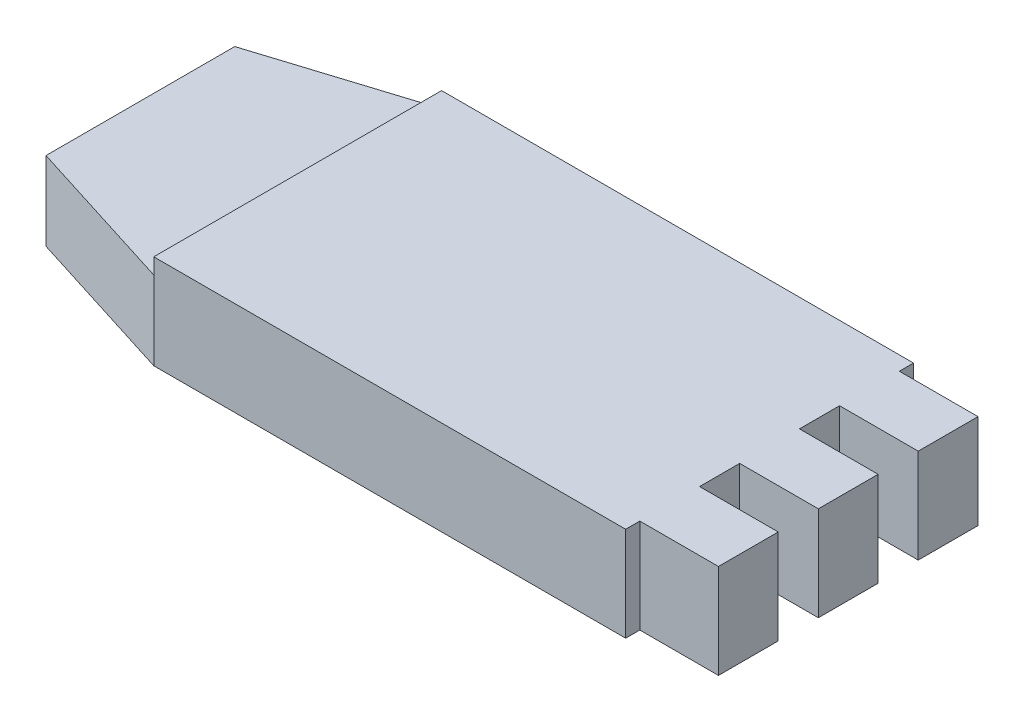
SolidWorks part; units mm, degrees
ref_plane "Front Plane" through (0, 0, 0) normal (0, 0, 1) x (1, 0, 0)
ref_plane "Top Plane" through (0, 0, 0) normal (0, 1, 0) x (1, 0, 0)
ref_plane "Right Plane" through (0, 0, 0) normal (1, 0, 0) x (0, 0, -1)
sketch "Sketch1" plane through (0, 0, 0) normal (0, 1, 0) x (1, 0, 0)
  line L0 (12.5, 9.15) -> (12.5, 8.25)
  line L1 (-17.5, -9.15) -> (17.5, -9.15)
  line L2 (-17.5, -9.15) -> (-17.5, 9.15)
  line L3 (-17.5, 9.15) -> (17.5, 9.15)
  line L4 (17.5, -9.15) -> (17.5, 9.15)
  line L5 (0, 9.15) -> (0, -9.15) construction
  line L6 (-17.5, 0) -> (17.5, 0) construction
  line L7 (12.5, 8.25) -> (17.5, 8.25)
  line L8 (12.5, -8.25) -> (17.5, -8.25)
  line L9 (15, -8.25) -> (15, 8.25) construction
  line L10 (12.5, 4.45) -> (17.5, 4.45)
  line L11 (12.5, -4.45) -> (17.5, -4.45)
  line L12 (15, -1.9) -> (15, 1.9) construction
  line L13 (12.5, 1.9) -> (17.5, 1.9)
  line L14 (12.5, -1.9) -> (17.5, -1.9)
  line L15 (12.5, 4.45) -> (12.5, -9.15)
  point P0 (0, 0)
  point P13 (15, 0)
  point P20 (15, 0)
  point P24 (0, 0)
  point P25 (0, 0)
  dimension "D1" = 18.3
  dimension "D2" = 35
  dimension "D3" = 5
  dimension "D4" = 16.5
  dimension "D5" = 3.8
  dimension "D6" = 3.8
extrude "Boss-Extrude1" add sketch "Sketch1" along normal blind 6 contours L15 L10 L4 L7 L0 L3 L2 L1 | L13 L15 L14 L4 | L11 L15 L8 L4
sketch "Sketch2" plane through (0, 0, 0) normal (0, 1, 0) x (1, 0, 0)
  line L0 (-17.5, 9.15) -> (-17.5, -9.15)
  line L1 (-17.5, 0) -> (-27.5, 0)
  line L2 (-27.5, -6) -> (-27.5, 6)
  line L3 (-27.5, 6) -> (-17.5, 9.15)
  line L4 (-27.5, -6) -> (-17.5, -9.15)
  point P0 (-17.5, 9.15)
  point P1 (-17.5, -9.15)
  point P6 (-17.5, 0)
  point P13 (-27.5, 0)
  dimension "D1" = 12
  dimension "D2" = 10
extrude "Boss-Extrude2" add sketch "Sketch2" along normal blind 5 contours L3 L2 L1 L0 | L2 L4 L0 L1
